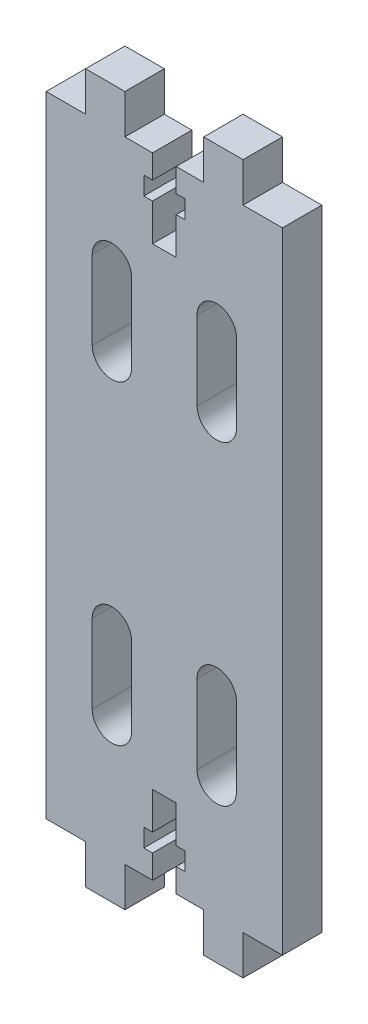
SolidWorks part; units mm, degrees
ref_plane "Front Plane" through (0, 0, 0) normal (0, 0, 1) x (1, 0, 0)
ref_plane "Top Plane" through (0, 0, 0) normal (0, 1, 0) x (1, 0, 0)
ref_plane "Right Plane" through (0, 0, 0) normal (1, 0, 0) x (0, 0, -1)
sketch "Sketch1" plane through (0, 0, 0) normal (0, 0, 1) x (1, 0, 0)
  line L0 (0, 72.0719) -> (0, -22.2682) construction
  line L1 (-15, 40) -> (-15, -40)
  line L2 (15, 40) -> (15, -40)
  line L3 (0, 0) -> (45.6439, 0) construction
  line L4 (-15, 40) -> (15, 40)
  line L5 (-15, -40) -> (15, -40)
  line L6 (-6.6565, -25) -> (-6.6565, -15) construction
  line L7 (-9.1565, -25) -> (-9.1565, -15)
  line L8 (-4.1565, -25) -> (-4.1565, -15)
  line L9 (6.6565, -25) -> (6.6565, -15) construction
  line L10 (9.1565, -25) -> (9.1565, -15)
  line L11 (4.1565, -25) -> (4.1565, -15)
  line L12 (6.6565, 25) -> (6.6565, 15) construction
  line L13 (9.1565, 25) -> (9.1565, 15)
  line L14 (4.1565, 25) -> (4.1565, 15)
  line L15 (-6.6565, 25) -> (-6.6565, 15) construction
  line L16 (-9.1565, 25) -> (-9.1565, 15)
  line L17 (-4.1565, 25) -> (-4.1565, 15)
  arc A0 (-9.1565, -25) -> (-4.1565, -25) centre (-6.6565, -25) ccw
  arc A1 (-4.1565, -15) -> (-9.1565, -15) centre (-6.6565, -15) ccw
  arc A2 (9.1565, -25) -> (4.1565, -25) centre (6.6565, -25) cw
  arc A3 (4.1565, -15) -> (9.1565, -15) centre (6.6565, -15) cw
  arc A4 (9.1565, 25) -> (4.1565, 25) centre (6.6565, 25) ccw
  arc A5 (4.1565, 15) -> (9.1565, 15) centre (6.6565, 15) ccw
  arc A6 (-9.1565, 25) -> (-4.1565, 25) centre (-6.6565, 25) cw
  arc A7 (-4.1565, 15) -> (-9.1565, 15) centre (-6.6565, 15) cw
  point P11 (-6.6565, -20)
  point P16 (0, 0)
  point P17 (0, 0)
  point P18 (0, 0)
  point P19 (0, 0)
  point P22 (6.6565, -20)
  point P29 (6.6565, 20)
  point P36 (-6.6565, 20)
  line B0 (-2.6, -37) -> (-2.6, -34.7)
  line B1 (1.5, -34.7) -> (1.5, -30)
  line B2 (-1.5, -30) -> (-1.5, -34.7)
  line B3 (-2.6, -34.7) -> (-1.5, -34.7)
  line B4 (0, -40) -> (0, -28.7792) construction
  line B5 (-1.5, -40) -> (-5, -40)
  line B6 (-5, -45) -> (-10, -45)
  line B7 (-10, -45) -> (-10, -40)
  line B8 (-5, -45) -> (-5, -40)
  line B9 (1.5, -40) -> (5, -40)
  line B10 (5, -40) -> (5, -45)
  line B11 (5, -45) -> (10, -45)
  line B12 (10, -45) -> (10, -40)
  line B13 (1.5, -40) -> (1.5, -37)
  line B14 (0, -30) -> (0, -40) construction
  line B15 (-1.5, -37) -> (-1.5, -40)
  line B16 (2.6, -34.7) -> (2.6, -37)
  line B17 (-1.5, -40) -> (1.5, -40) construction
  line B18 (1.5, -34.7) -> (2.6, -34.7)
  line B19 (2.6, -37) -> (1.5, -37)
  line B20 (1.5, -30) -> (-1.5, -30)
  line B21 (-1.5, -37) -> (-2.6, -37)
  line B22 (2.6, 37) -> (2.6, 34.7)
  line B23 (-1.5, 34.7) -> (-1.5, 30)
  line B24 (1.5, 30) -> (1.5, 34.7)
  line B25 (2.6, 34.7) -> (1.5, 34.7)
  line B26 (0, 40) -> (0, 28.7792) construction
  line B27 (1.5, 40) -> (5, 40)
  line B28 (5, 45) -> (10, 45)
  line B29 (10, 45) -> (10, 40)
  line B30 (5, 45) -> (5, 40)
  line B31 (-1.5, 40) -> (-5, 40)
  line B32 (-5, 40) -> (-5, 45)
  line B33 (-5, 45) -> (-10, 45)
  line B34 (-10, 45) -> (-10, 40)
  line B35 (-1.5, 40) -> (-1.5, 37)
  line B36 (0, 30) -> (0, 40) construction
  line B37 (1.5, 37) -> (1.5, 40)
  line B38 (-2.6, 34.7) -> (-2.6, 37)
  line B39 (1.5, 40) -> (-1.5, 40) construction
  line B40 (-1.5, 34.7) -> (-2.6, 34.7)
  line B41 (-2.6, 37) -> (-1.5, 37)
  line B42 (-1.5, 30) -> (1.5, 30)
  line B43 (1.5, 37) -> (2.6, 37)
  dimension "D1" = 80
  dimension "D2" = 5
  dimension "D3" = 30
  dimension "D4" = 10
  dimension "D5" = 20
sketch_block_instance "Insert M3 plots ep 5mm-1"
sketch_block "Insert M3 plots ep 5mm" parameters "D1"=10, "D2"=5, "D3"=5
sketch_block_instance "Decoupe Insert M3-4"
sketch_block "Decoupe Insert M3" parameters "D1"=5.2, "D2"=3, "D3"=2.3, "D4"=3, "D5"=10
sketch_block_instance "Insert M3 plots ep 5mm-2"
extrude "Boss-Extrude1" add sketch "Sketch1" along normal blind 5 contours B28 B30 L4 B29 | B37 B43 B22 B25 B24 B42 B23 B40 B38 B41 B35 L4 L1 L5 B15 B21 B0 B3 B2 B20 B1 B18 B16 B19 B13 L2 | B33 B34 L4 B32 | B6 B8 L5 B7 | B11 B12 L5 B10
